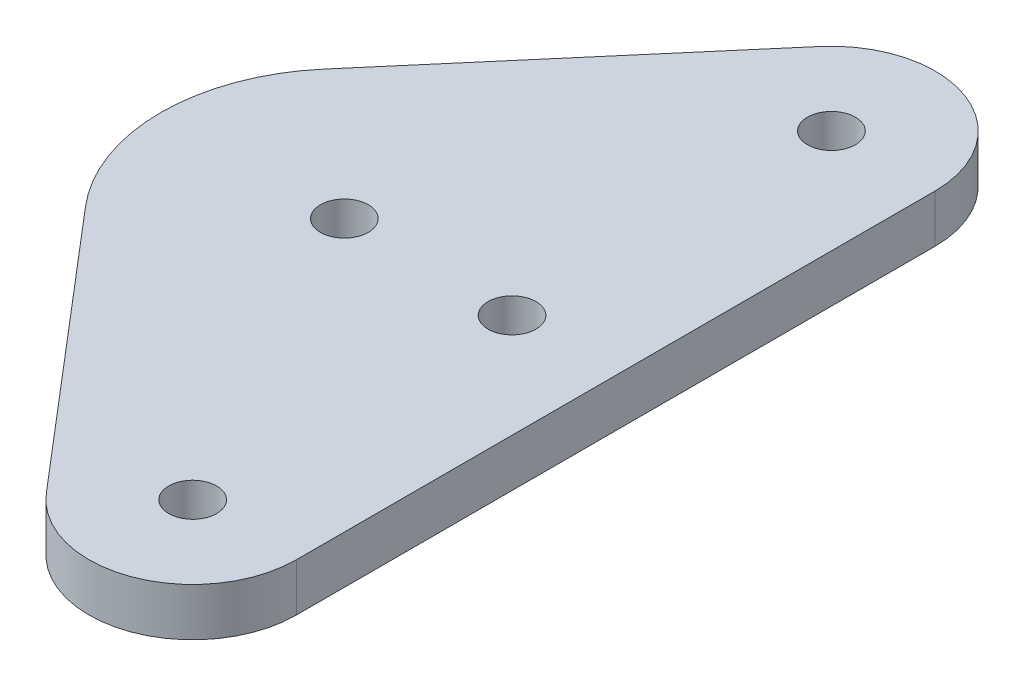
SolidWorks part; units mm, degrees
ref_plane "正面" through (0, 0, 0) normal (0, 0, 1) x (1, 0, 0)
ref_plane "平面" through (0, 0, 0) normal (0, 1, 0) x (1, 0, 0)
ref_plane "右側面" through (0, 0, 0) normal (1, 0, 0) x (0, 0, -1)
sketch "ｽｹｯﾁ1" plane through (0, 0, 0) normal (0, 1, 0) x (1, 0, 0)
  line L0 (6.5, 20) -> (6.5, 0)
  line L1 (6.5, 0) -> (6.5, -20)
  line L2 (-4.9435, 24.2204) -> (-19.2463, 7.4668)
  line L3 (-19.2463, -7.4668) -> (-4.9435, -24.2204)
  circle A0 centre (0, 0) radius 1.5
  circle A1 centre (0, 20) radius 1.5
  circle A2 centre (0, -20) radius 1.5
  arc A5 (6.5, 20) -> (-4.9435, 24.2204) centre (0, 20) ccw
  arc A6 (-4.9435, -24.2204) -> (6.5, -20) centre (0, -20) ccw
  arc A8 (-19.2463, 7.4668) -> (-19.2463, -7.4668) centre (-10.5, 0) ccw
  circle A9 centre (-10.5, 0) radius 1.5
  point P9 (0, 0)
  point P11 (0, 0)
  point P14 (0, 0)
  point P19 (0, 0)
  point P20 (0, 0)
  point P22 (0, 0)
  point P23 (0, 0)
  point P24 (6.0642, 0)
  dimension "D1" = 3
  dimension "D4" = 5
  dimension "D7" = 10.5
  dimension "D5" = 10
  dimension "D6" = 6.5
  dimension "D2" = 20
  dimension "D3" = 20
extrude "ﾎﾞｽ - 押し出し1" add sketch "ｽｹｯﾁ1" along normal blind 3
